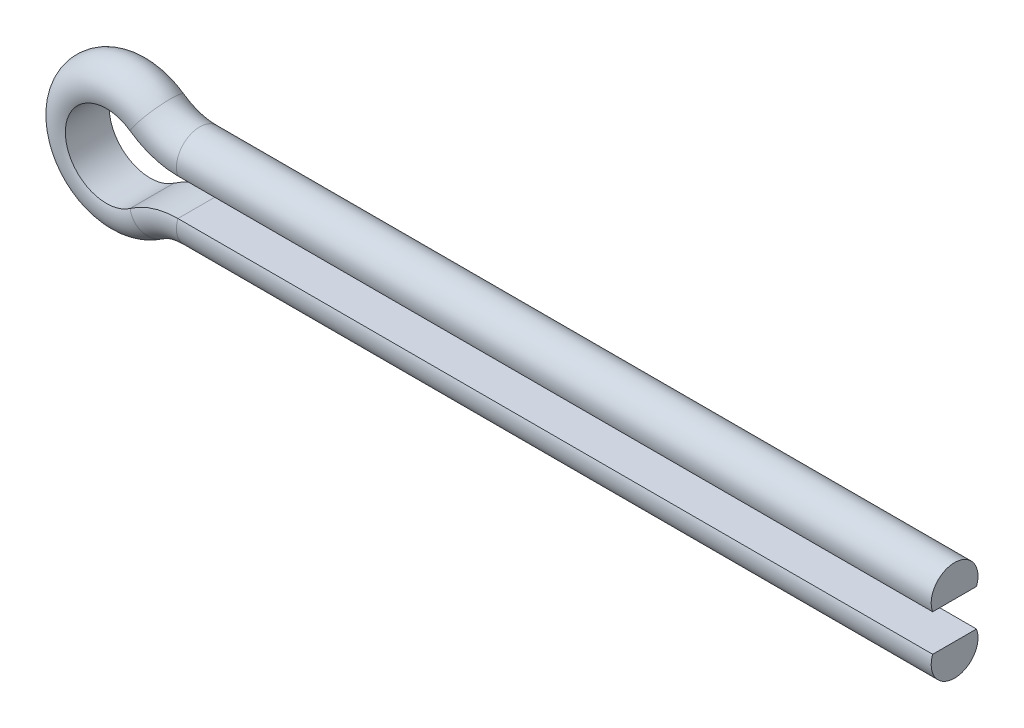
SolidWorks part; units mm, degrees
ref_plane "Front Plane" through (0, 0, 0) normal (0, 0, 1) x (1, 0, 0)
ref_plane "Top Plane" through (0, 0, 0) normal (0, 1, 0) x (1, 0, 0)
ref_plane "Right Plane" through (0, 0, 0) normal (1, 0, 0) x (0, 0, -1)
sketch "Sketch1" plane through (0, 0, 0) normal (0, 0, 1) x (1, 0, 0)
  line L0 (0, 0) -> (98.9392, 0) construction
  line L1 (8.6531, 2.2525) -> (100, 2.2525)
  line L2 (8.6531, -2.2525) -> (100, -2.2525)
  arc A0 (2.8844, 4.0842) -> (2.8844, -4.0842) centre (0, 0) ccw
  arc A1 (2.8844, -4.0842) -> (8.6531, -2.2525) centre (8.6531, -12.2525) cw
  arc A2 (8.6531, 2.2525) -> (2.8844, 4.0842) centre (8.6531, 12.2525) cw
  point P9 (4.4639, -2.2525)
  point P12 (4.4639, 2.2525)
  dimension "D1" = 10
  dimension "D3" = 10
  dimension "D2" = 100
ref_plane "Plane1" through (100, 2.2525, 0) normal (1, 0, 0) x (0, 0, -1)
sketch "Sketch2" plane through (100, 2.2525, 0) normal (1, 0, 0) x (0, 0, -1)
  line L0 (2.6514, -0.0265) -> (-2.6514, -0.0265)
  arc A0 (2.6514, -0.0265) -> (-2.6514, -0.0265) centre (0, 0.9735) ccw
  dimension "D1" = 1
sweep "Sweep1" add profiles "Sketch2" path "Sketch1"
